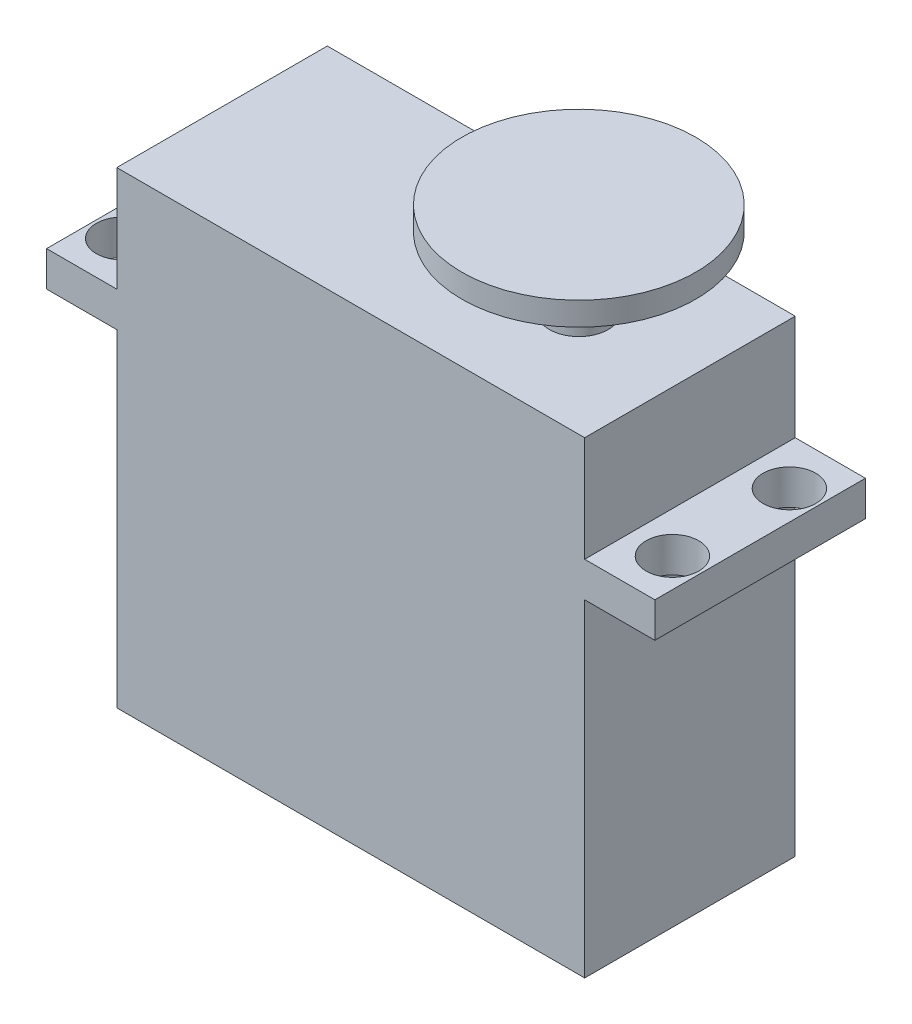
SolidWorks part; units mm, degrees
ref_plane "Front Plane" through (0, 0, 0) normal (0, 0, 1) x (1, 0, 0)
ref_plane "Top Plane" through (0, 0, 0) normal (0, 1, 0) x (1, 0, 0)
ref_plane "Right Plane" through (0, 0, 0) normal (1, 0, 0) x (0, 0, -1)
sketch "Sketch1" plane through (0, 0, 0) normal (0, 1, 0) x (1, 0, 0)
  line L1 (0, 0) -> (40, 0)
  line L2 (0, 0) -> (0, 18)
  line L3 (0, 18) -> (40, 18)
  line L4 (40, 0) -> (40, 18)
  dimension "D1" = 40
  dimension "D2" = 18
extrude "Boss-Extrude1" add sketch "Sketch1" along normal blind 40
ref_plane "Plane1" through (0, 28, 0) normal (0, -1, 0) x (-1, 0, 0)
sketch "Sketch2" plane through (0, 28, 0) normal (0, -1, 0) x (-1, 0, 0)
  line L1 (-40, 0) -> (-46, 0)
  line L2 (-40, 0) -> (-40, 18)
  line L3 (-40, 18) -> (-46, 18)
  line L4 (-46, 0) -> (-46, 18)
  line L5 (0, 18) -> (6, 18)
  line L6 (0, 18) -> (0, 0)
  line L7 (0, 0) -> (6, 0)
  line L8 (0, 0) -> (0, 18)
  line L9 (-40, 0) -> (0, 0)
  line L10 (-40, 18) -> (-40, 0)
  line L11 (0, 18) -> (-40, 18)
  line L12 (0, 0) -> (0, 18)
  line L13 (-40, 0) -> (0, 0)
  line L14 (-40, 18) -> (-40, 0)
  line L15 (0, 18) -> (-40, 18)
  line L16 (6, 18) -> (6, 0)
  dimension "D2" = 6
  dimension "D3" = 6
  dimension "D1" = 0
extrude "Boss-Extrude2" add sketch "Sketch2" against normal blind 3 contours L16 L5 L6 L7 | L4 L1 L2 L3
sketch "Sketch3" plane through (0, 40, 0) normal (0, 1, 0) x (1, 0, 0)
  line L0 (30.5, 18) -> (30.5, 0) construction
  line L1 (40, 18) -> (0, 18) construction
  line L2 (0, 0) -> (40, 0) construction
  line L3 (40, 0) -> (40, 18) construction
  circle A0 centre (30.5, 9) radius 2.5
  dimension "D1" = 9.5
extrude "Boss-Extrude3" add sketch "Sketch3" along normal blind 6
sketch "Sketch4" plane through (0, 46, 0) normal (0, 1, 0) x (1, 0, 0)
  circle A0 centre (30.5, 9) radius 10
extrude "Boss-Extrude4" add sketch "Sketch4" along normal blind 2
sketch "Sketch5" plane through (0, 31, 0) normal (0, 1, 0) x (1, 0, 0)
  line L0 (0, 0) -> (-6, 0) construction
  line L4 (0, 18) -> (0, 0) construction
  line L5 (-3.5, 14) -> (-3.5, 4) construction
  circle A0 centre (-3.5, 14) radius 2.25
  circle A1 centre (-3.5, 4) radius 2.25
  dimension "D1" = 10
  dimension "D4" = 4.5
  dimension "D5" = 4.5
  dimension "D2" = 4
  dimension "D3" = 3.5
ref_plane "Plane2" through (20, 0, 0) normal (-1, 0, 0) x (0, 0, 1)
extrude "Cut-Extrude1" cut sketch "Sketch5" against normal up to next
mirror "Mirror1" about plane through (20, 0, 0) normal (-1, 0, 0) of "Cut-Extrude1"
